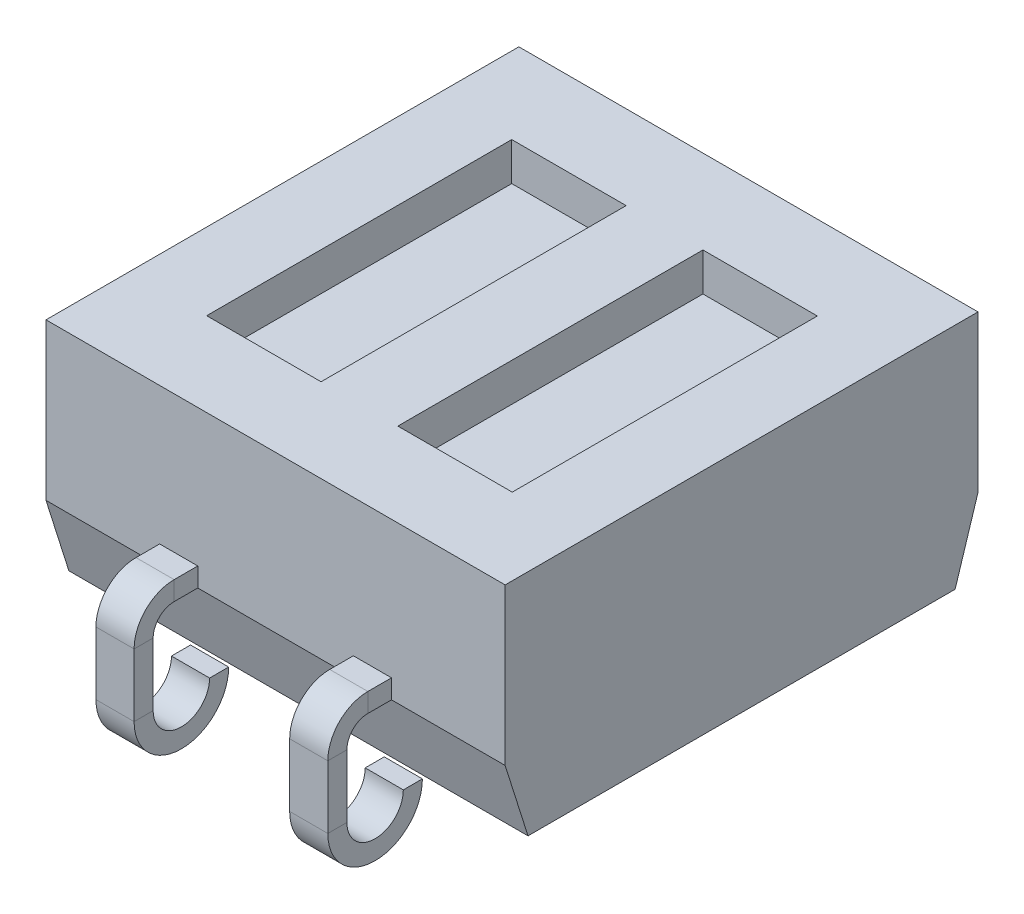
SolidWorks part; units mm, degrees
ref_plane "Спереди" through (0, 0, 0) normal (0, 0, 1) x (1, 0, 0)
ref_plane "Сверху" through (0, 0, 0) normal (0, 1, 0) x (1, 0, 0)
ref_plane "Справа" through (0, 0, 0) normal (1, 0, 0) x (0, 0, -1)
sketch "Эскиз3" plane through (0, 0, 0) normal (0, 1, 0) x (1, 0, 0)
  line L1 (-3.01, -3.1) -> (3.01, -3.1)
  line L2 (-3.01, -3.1) -> (-3.01, 3.1)
  line L3 (-3.01, 3.1) -> (3.01, 3.1)
  line L4 (3.01, -3.1) -> (3.01, 3.1)
  line L5 (-3.01, -3.1) -> (3.01, 3.1) construction
  line L6 (-3.01, 3.1) -> (3.01, -3.1) construction
  point P0 (0, 0)
  dimension "D1" = 6.2
  dimension "D2" = 6.02
extrude "Бобышка-Вытянуть1" add sketch "Эскиз3" along normal blind 3
sketch "Эскиз4" plane through (0, 3, 0) normal (0, 1, 0) x (1, 0, 0)
  line L0 (-3.01, 0) -> (-2.0033, 0) construction
  line L1 (-3.01, 3.1) -> (-3.01, -3.1) construction
  line L2 (-0.5033, 0) -> (0.5033, 0) construction
  line L4 (2.0033, 0) -> (3.01, 0) construction
  line L5 (3.01, -3.1) -> (3.01, 3.1) construction
  line L8 (-2.0033, -2) -> (-0.5033, -2)
  line L9 (-2.0033, -2) -> (-2.0033, 2)
  line L10 (-2.0033, 2) -> (-0.5033, 2)
  line L11 (-0.5033, -2) -> (-0.5033, 2)
  line L12 (-2.0033, -2) -> (-0.5033, 2) construction
  line L13 (-2.0033, 2) -> (-0.5033, -2) construction
  line L14 (0.5033, -2) -> (2.0033, -2)
  line L15 (0.5033, -2) -> (0.5033, 2)
  line L16 (0.5033, 2) -> (2.0033, 2)
  line L17 (2.0033, -2) -> (2.0033, 2)
  line L18 (0.5033, -2) -> (2.0033, 2) construction
  line L19 (0.5033, 2) -> (2.0033, -2) construction
  point P10 (-0.4427, 2.1128)
  point P14 (-1.2533, 0)
  point P19 (1.2533, 0)
  dimension "D1" = 4
  dimension "D2" = 1.5
extrude "Вырез-Вытянуть1" cut sketch "Эскиз4" against normal blind 0.5
sketch "Эскиз5" plane through (3.01, 0, 0) normal (1, 0, 0) x (0, 0, -1)
  line L0 (-3.1, 0.95) -> (-2.8, 0)
  line L1 (-3.1, 3) -> (-3.1, 0) construction
  line L2 (-3.1, 0) -> (3.1, 0) construction
  line L3 (-2.8, 0) -> (-3.1, 0)
  line L4 (-3.1, 0) -> (-3.1, 0.95)
  line L5 (3.1, 0) -> (2.8, 0)
  line L6 (2.8, 0) -> (3.1, 0.95)
  line L7 (3.1, 3) -> (3.1, 0) construction
  line L8 (3.1, 0.95) -> (3.1, 0)
  line L9 (-3.1, 3) -> (3.1, 3) construction
  dimension "D1" = 2.05
  dimension "D2" = 0.3
extrude "Вырез-Вытянуть2" cut sketch "Эскиз5" against normal through all
sketch3d "Трехмерный эскиз1"
  line L0 (-3.01, 3, 3.1) -> (-1.27, 3, 3.1) construction
  line L1 (-3.01, 3, 3.1) -> (3.01, 3, 3.1) construction
  line L2 (-1.27, 1.075, 3.1) -> (-1.27, 1.075, 0) construction
  line L3 (-1.27, 0.675, 3.81) -> (-1.27, -0.15, 3.81)
  line L4 (-1.27, -0.15, 2.82) -> (-1.27, -0.15, 3.81) construction
  line L5 (-1.27, 1.075, 3.1) -> (-1.27, 1.075, 3.41)
  line L6 (-1.27, 3, 3.1) -> (-1.27, 4, 3.1) construction
  line L7 (-1.27, 0.95, 3.1) -> (-1.27, 1.2, 3.1) construction
  line L8 (-1.27, -0.77, 3.315) -> (-1.27, -0.52, 3.315) construction
  line L9 (-1.27, -0.15, 2.945) -> (-1.27, -0.15, 2.695) construction
  line L10 (-1.27, 3, 3.1) -> (-1.27, 1.075, 3.1) construction
  line L11 (-1.27, -0.15, 3.685) -> (-1.27, -0.15, 3.935) construction
  line L12 (-1.27, -0.15, 3.315) -> (-1.27, -0.645, 3.315) construction
  line L14 (-3.01, 3, -3.1) -> (-3.01, 3, 3.1) construction
  line L15 (-3.01, 1.075, 0) -> (-1.27, 1.075, 0) construction
  line L16 (-1.27, 1.075, 0) -> (-1.27, 0, 0) construction
  line L17 (-3.01, 1.075, 0) -> (-3.01, 3, 0) construction
  line L18 (-1.27, 1.2, 3.1) -> (-1.27, 1.2, 4.1) construction
  line L19 (-1.27, -0.77, 3.315) -> (-1.27, -0.77, 4.1) construction
  line L20 (-1.27, -0.77, 4.1) -> (-1.27, 1.2, 4.1) construction
  arc A0 (-1.27, 1.075, 3.41) -> (-1.27, 0.675, 3.81) centre (-1.27, 0.675, 3.41) ccw
  arc A1 (-1.27, -0.15, 3.81) -> (-1.27, -0.15, 2.82) centre (-1.27, -0.15, 3.315) ccw
  point P8 (-1.27, 1.075, 3.4313)
  point P16 (-0.87, 0.675, 3.41)
  point P18 (-0.775, -0.15, 3.315)
  point P22 (-1.27, 1.075, 3.1)
  point P26 (-1.27, -0.645, 3.315)
  point P28 (-1.27, -0.15, 2.82)
  point P30 (-1.27, -0.15, 3.81)
  point P35 (-1.27, 1.2, 4.2641)
  dimension "D2" = 3.935
  dimension "D10" = 0.4
  dimension "D1" = 1.74
  dimension "D4" = 1
  dimension "D3" = 1.97
  dimension "D8" = 3.315
  dimension "D6" = 1.8
  dimension "D5" = 0.77
  dimension "D7" = 0.25
  dimension "D9" = 0.15
sketch "Эскиз6" plane through (0, 0, 3.1) normal (0, 0, 1) x (1, 0, 0)
  line L1 (-1.52, 0.95) -> (-1.02, 0.95)
  line L2 (-1.52, 0.95) -> (-1.52, 1.2)
  line L3 (-1.52, 1.2) -> (-1.02, 1.2)
  line L4 (-1.02, 0.95) -> (-1.02, 1.2)
  line L5 (-1.52, 0.95) -> (-1.02, 1.2) construction
  line L6 (-1.52, 1.2) -> (-1.02, 0.95) construction
  point P0 (-1.27, 1.075)
  dimension "D1" = 0.5
sweep "По траектории1" add profiles "Эскиз6" path "Трехмерный эскиз1"
pattern_linear "Линейный массив1" count 2 spacing 2.54 along (1, 0, 0) of "По траектории1"
mirror "Зеркальное отражение1" about plane through (0, 0, 0) normal (0, 0, 1) of "Линейный массив1", "По траектории1"
